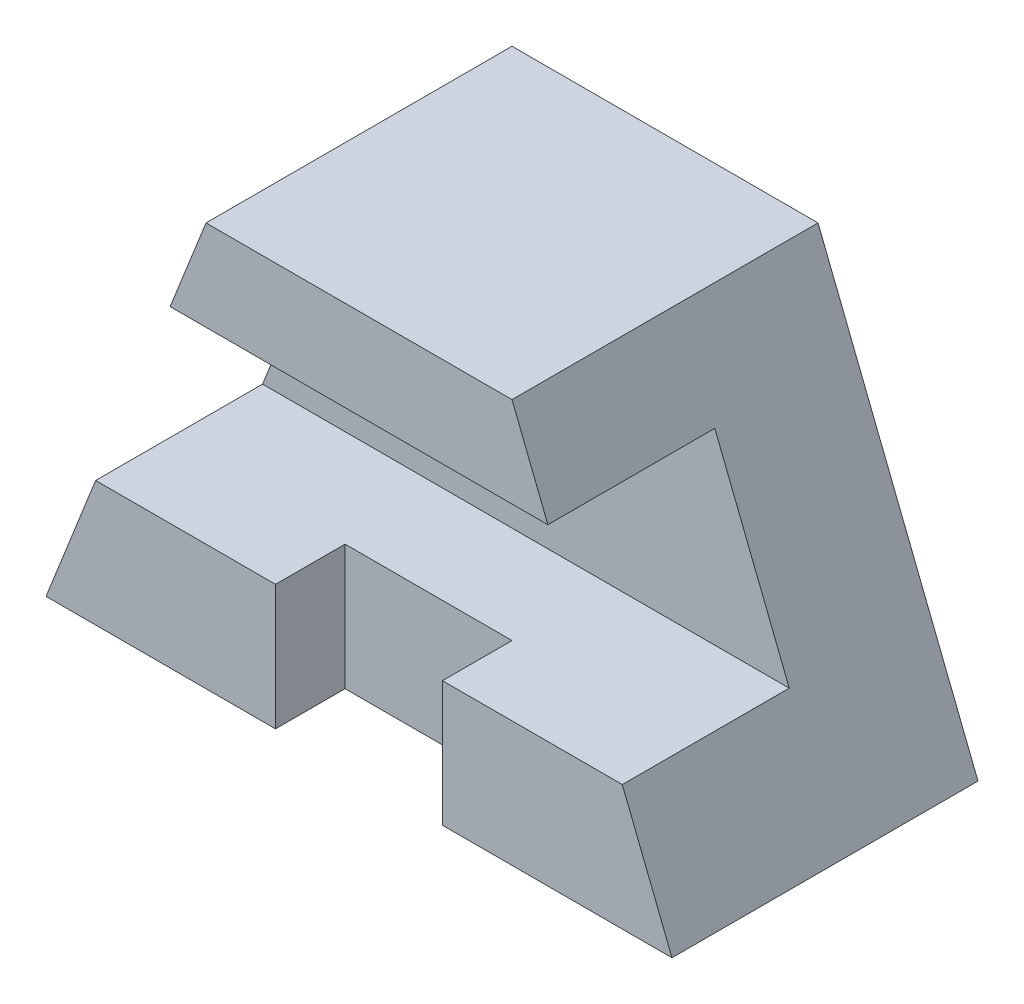
SolidWorks part; units mm, degrees
ref_plane "Front Plane" through (0, 0, 0) normal (0, 0, 1) x (1, 0, 0)
ref_plane "Top Plane" through (0, 0, 0) normal (0, 1, 0) x (1, 0, 0)
ref_plane "Right Plane" through (0, 0, 0) normal (1, 0, 0) x (0, 0, -1)
sketch "Sketch1" plane through (0, 0, 0) normal (0, 0, 1) x (1, 0, 0)
  line L1 (45, 58) -> (-45, 58)
  line L2 (45, 58) -> (45, 0)
  line L3 (45, 0) -> (-45, 0)
  line L4 (-45, 58) -> (-45, 0)
  line L5 (45, 58) -> (-45, 0) construction
  line L6 (45, 0) -> (-45, 58) construction
  point P0 (0, 29)
  point P6 (0, 0)
  dimension "D1" = 90
  dimension "D2" = 58
extrude "Boss-Extrude1" add sketch "Sketch1" along normal mid plane 44
sketch "Sketch2" plane through (0, 0, 22) normal (0, 0, 1) x (1, 0, 0)
  line L0 (-45, 58) -> (-45, 0) construction
  line L1 (-45, 18) -> (45, 18)
  line L2 (-45, 18) -> (-45, 45)
  line L3 (-45, 45) -> (45, 45)
  line L4 (45, 18) -> (45, 45)
  line L5 (-45, 18) -> (45, 45) construction
  line L6 (-45, 45) -> (45, 18) construction
  line L7 (-45, 0) -> (45, 0) construction
  point P0 (0, 31.5)
  point P5 (0, 0)
  dimension "D1" = 18
  dimension "D2" = 27
extrude "Cut-Extrude1" cut sketch "Sketch2" against normal blind 24
sketch "Sketch3" plane through (0, 0, -22) normal (0, 0, -1) x (-1, 0, 0)
  line L0 (-45, 58) -> (-45, 0)
  line L1 (-45, 0) -> (-22, 58)
  line L2 (-45, 58) -> (45, 58) construction
  line L3 (-22, 58) -> (-45, 58)
  dimension "D1" = 23
extrude "Cut-Extrude2" cut sketch "Sketch3" against normal through all
mirror "Mirror1" about plane through (0, 0, 0) normal (1, 0, 0) of "Cut-Extrude2"
sketch "Sketch4" plane through (0, 0, 0) normal (0, -1, 0) x (1, 0, 0)
  line L0 (-45, 22) -> (45, 22) construction
  line L1 (-12, 12) -> (12, 12)
  line L2 (-12, 12) -> (-12, 22)
  line L3 (-12, 22) -> (12, 22)
  line L4 (12, 12) -> (12, 22)
  line L5 (-12, 12) -> (12, 22) construction
  line L6 (-12, 22) -> (12, 12) construction
  point P0 (0, 17)
  point P7 (0, 0)
  dimension "D1" = 10
  dimension "D2" = 24
extrude "Cut-Extrude3" cut sketch "Sketch4" against normal up to next
